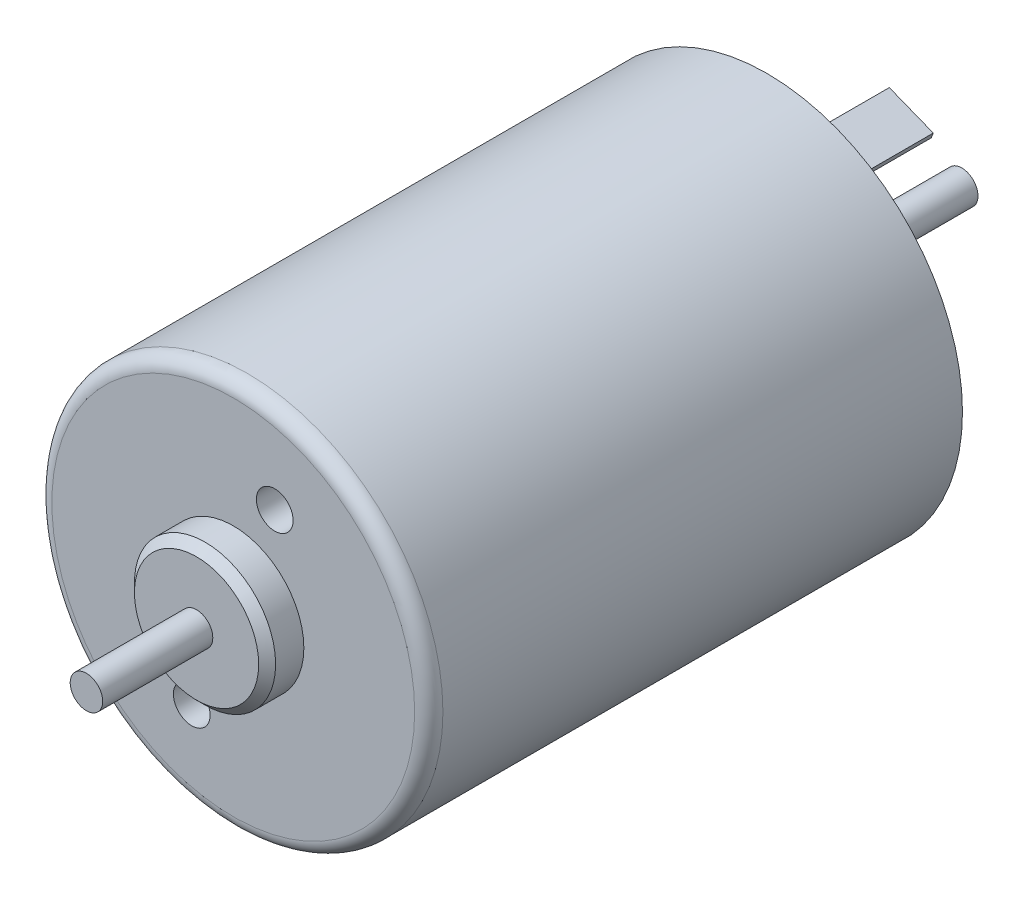
SolidWorks part; units mm, degrees
ref_plane "Front Plane" through (0, 0, 0) normal (0, 0, 1) x (1, 0, 0)
ref_plane "Top Plane" through (0, 0, 0) normal (0, 1, 0) x (1, 0, 0)
ref_plane "Right Plane" through (0, 0, 0) normal (1, 0, 0) x (0, 0, -1)
ref_plane "Plane1" through (0, 0, 0) normal (0, -1, 0) x (1, 0, 0)
sketch "Sketch1" plane through (0, 0, 0) normal (0, -1, 0) x (1, 0, 0)
  line L0 (13.85, 32.9) -> (0, 32.9)
  line L1 (0, 32.9) -> (0, 12.9)
  line L2 (0, 12.9) -> (13.85, 12.9)
  line L3 (13.85, 12.9) -> (13.85, 32.9)
  line L4 (0, 32.9) -> (0, 12.9) construction
  dimension "D1" = 20
  dimension "D2" = 13.85
revolve "Revolve1" add sketch "Sketch1" angle 360 about L4
sketch "Sketch2" plane through (0, 0, 12.9) normal (0, 0, -1) x (-1, 0, 0)
  circle A0 centre (0, 0) radius 13.85
  dimension "D1" = 27.7
extrude "Boss-Extrude1" add sketch "Sketch2" along normal blind 12.9
sketch "Sketch3" plane through (0, 0, 0) normal (0, 0, -1) x (-1, 0, 0)
  line L0 (-5.7826, 10.0805) -> (-2.6669, 11.3112)
  line L1 (-2.6669, 11.3112) -> (-2.5199, 10.9392)
  line L2 (-2.5199, 10.9392) -> (-5.6357, 9.7085)
  line L3 (-5.6357, 9.7085) -> (-5.7826, 10.0805)
extrude "Boss-Extrude2" add sketch "Sketch3" along normal blind 6
sketch "Sketch4" plane through (0, 0, 0) normal (0, 0, -1) x (-1, 0, 0)
  line L0 (2.5199, -10.9392) -> (5.6357, -9.7085)
  line L1 (5.6357, -9.7085) -> (5.7826, -10.0805)
  line L2 (5.7826, -10.0805) -> (2.6669, -11.3112)
  line L3 (2.6669, -11.3112) -> (2.5199, -10.9392)
extrude "Boss-Extrude3" add sketch "Sketch4" along normal blind 6
sketch "Sketch5" plane through (0, 0, 32.9) normal (0, 0, 1) x (1, 0, 0)
  circle A0 centre (0, 0) radius 13.85
extrude "Boss-Extrude4" add sketch "Sketch5" along normal blind 4.9
sketch "Sketch6" plane through (0, 0, 37.8) normal (0, 0, 1) x (1, 0, 0)
  circle A0 centre (0, 0) radius 5
extrude "Boss-Extrude5" add sketch "Sketch6" along normal blind 2.6
sketch "Sketch7" plane through (0, 0, 40.4) normal (0, 0, 1) x (1, 0, 0)
  circle A0 centre (0, 0) radius 1.15
extrude "Boss-Extrude6" add sketch "Sketch7" along normal blind 7.8
sketch "Sketch8" plane through (0, 0, 0) normal (0, 0, -1) x (-1, 0, 0)
  circle A0 centre (0, 0) radius 5
extrude "Boss-Extrude7" add sketch "Sketch8" along normal blind 2.6
sketch "Sketch9" plane through (0, 0, -2.6) normal (0, 0, -1) x (-1, 0, 0)
  circle A0 centre (0, 0) radius 1.15
extrude "Boss-Extrude8" add sketch "Sketch9" along normal blind 11.2
hole_wizard "Ø2.6 (2.6) Diameter Hole1" positions "Sketch11" profile "Sketch10" hole size "Ø2.6" standard "ANSI Metric"
sketch "Sketch11" plane through (0, 0, 37.8) normal (0, 0, 1) x (1, 0, 0)
  point P0 (-2.9389, -7.4406)
  point P1 (2.9389, 7.4406)
sketch "Sketch10" plane through (-2.9389, -7.4406, 37.8) normal (1, 0, 0) x (0, -1, 0)
  line L0 (0, 0) -> (0, 3.2163)
  line L1 (0, 3.2163) -> (1.3, 3.2163)
  line L2 (1.3, 3.2163) -> (1.3, 0)
  line L5 (1.3, 0) -> (0, 0)
  line L10 (0, 3.2163) -> (-1.3, 3.2163) construction
  line L11 (0, -6.35) -> (0, 107.95) construction
  dimension "Hole Dia." = 2.6
  dimension "Hole Depth" = 3.2163
  dimension "Drill Angle" = 180
chamfer "Chamfer1" distance 0.6 angle 45 2 edges at (0, 5, -2.6) (5, 0, 40.4)
fillet "Fillet1" radius 1 1 edges at (13.85, 0, 37.8)
